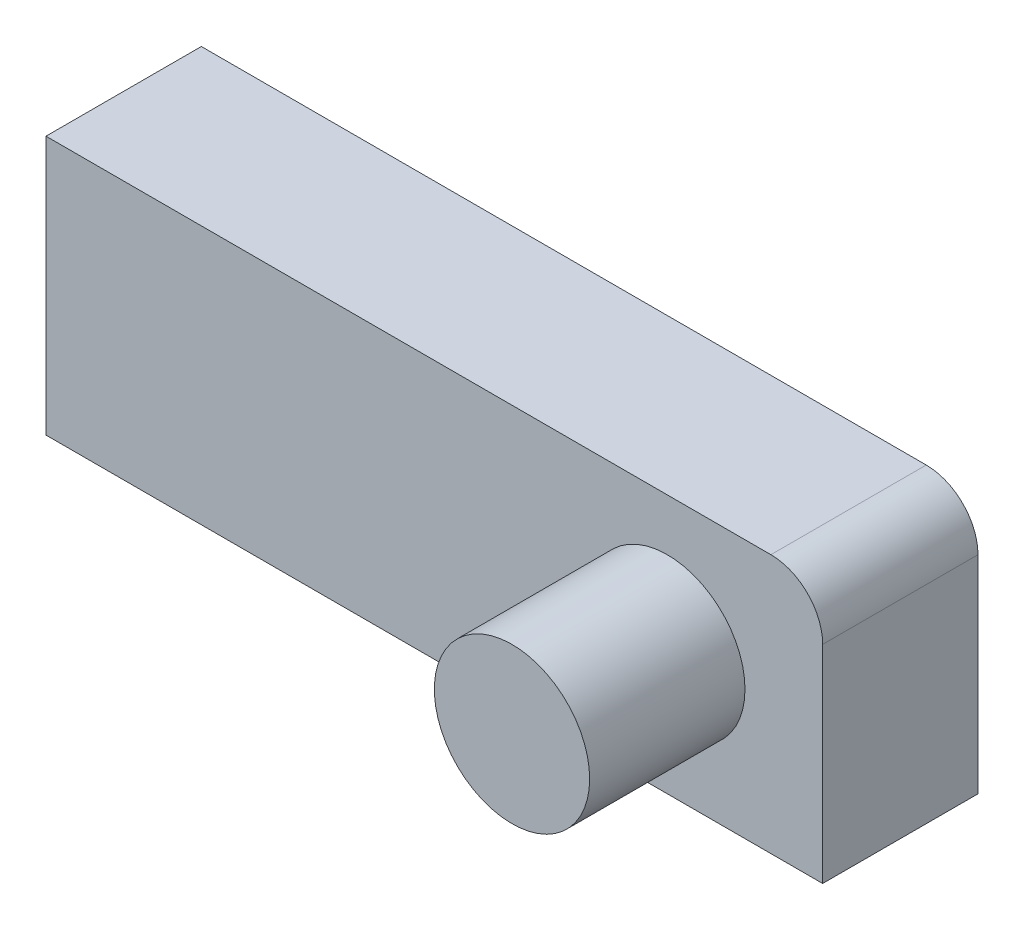
SolidWorks part; units mm, degrees
ref_plane "前视基准面" through (0, 0, 0) normal (0, 0, 1) x (1, 0, 0)
ref_plane "上视基准面" through (0, 0, 0) normal (0, 1, 0) x (1, 0, 0)
ref_plane "右视基准面" through (0, 0, 0) normal (1, 0, 0) x (0, 0, -1)
sketch "草图1" plane through (0, 0, 0) normal (0, 0, 1) x (1, 0, 0)
  line L1 (-16.7757, 4.2407) -> (-1.7757, 4.2407)
  line L2 (-16.7757, 4.2407) -> (-16.7757, -0.7593)
  line L3 (-16.7757, -0.7593) -> (-1.7757, -0.7593)
  line L4 (-1.7757, 4.2407) -> (-1.7757, -0.7593)
  line L5 (-16.7757, 4.2407) -> (-1.7757, -0.7593) construction
  line L6 (-16.7757, -0.7593) -> (-1.7757, 4.2407) construction
  point P0 (-9.2757, 1.7407)
  dimension "D1" = 15
  dimension "D2" = 5
extrude "凸台-拉伸1" add sketch "草图1" along normal blind 3
sketch "草图2" plane through (0, 0, 3) normal (0, 0, 1) x (1, 0, 0)
  line L0 (-1.7757, -0.7593) -> (-1.7757, 4.2407) construction
  line L1 (-1.7757, 4.2407) -> (-16.7757, 4.2407) construction
  circle A0 centre (-4.7757, 1.7407) radius 1.5
  dimension "D1" = 3
  dimension "D2" = 3
  dimension "D3" = 2.5
extrude "凸台-拉伸2" add sketch "草图2" along normal blind 3
fillet "圆角2" radius 1 1 edges at (-1.7757, 4.2407, 1.5)
